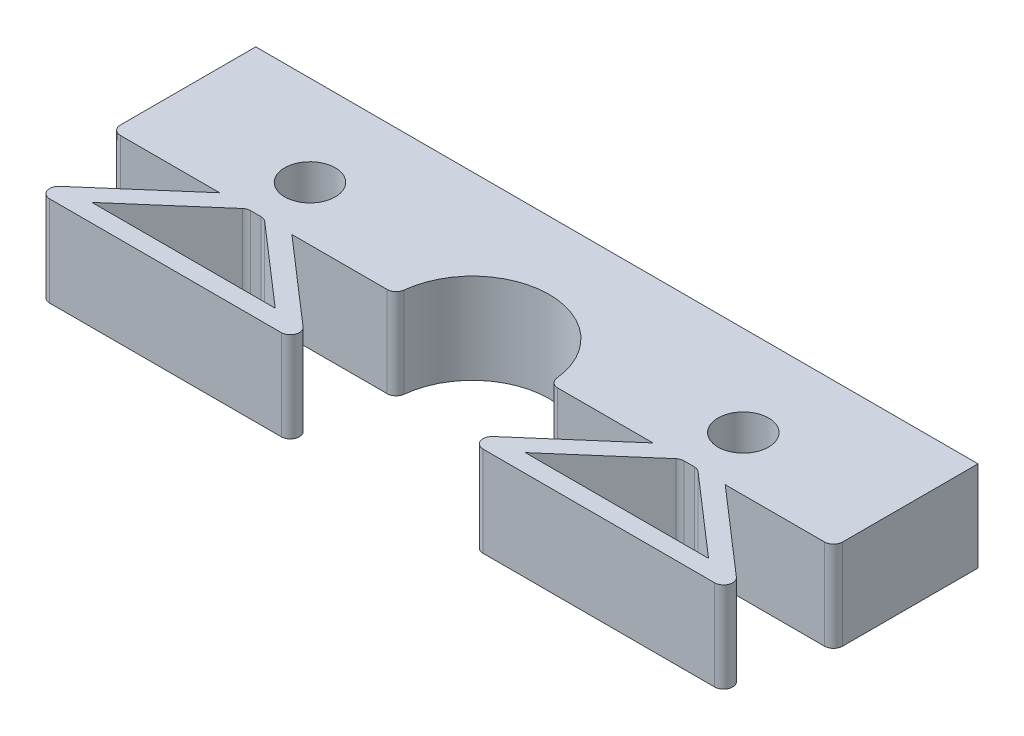
SolidWorks part; units mm, degrees
ref_plane "Front Plane" through (0, 0, 0) normal (0, 0, 1) x (1, 0, 0)
ref_plane "Top Plane" through (0, 0, 0) normal (0, 1, 0) x (1, 0, 0)
ref_plane "Right Plane" through (0, 0, 0) normal (1, 0, 0) x (0, 0, -1)
sketch "Sketch1" plane through (0, 0, 0) normal (0, 1, 0) x (1, 0, 0)
  line L1 (-20, 8) -> (20, 8)
  line L2 (20, 8) -> (20, 0)
  line L8 (4.25, -5) -> (10, 0)
  line L9 (10, 0) -> (-10, 0)
  line L10 (19.75, -5) -> (14, 0)
  line L11 (14, 0) -> (20, 0)
  line L15 (12.476, 0) -> (11.524, 0)
  line L17 (11.524, 0) -> (6.924, -4)
  line L18 (6.924, -4) -> (17.076, -4)
  line L19 (17.076, -4) -> (12.476, 0)
  line L20 (4.25, -5) -> (19.75, -5)
  line L21 (0, 8) -> (0, 0) construction
  line L23 (0, 0) -> (0, 20.8018) construction
  line L24 (-4.25, -5) -> (-10, 0)
  line L25 (-12.476, 0) -> (-11.524, 0)
  line L26 (-11.524, 0) -> (-6.924, -4)
  line L27 (-6.924, -4) -> (-17.076, -4)
  line L28 (-17.076, -4) -> (-12.476, 0)
  line L29 (-4.25, -5) -> (-19.75, -5)
  line L30 (-19.75, -5) -> (-14, 0)
  line L31 (-14, 0) -> (-20, 0)
  line L32 (-20, 8) -> (-20, 0)
  circle A0 centre (12, 3) radius 1.4
  circle A1 centre (-12, 3) radius 1.4
  point P0 (12, -5)
  point P1 (12, -4)
  point P4 (12, 0)
  point P30 (4, -6)
  point P31 (4, -6)
  point P34 (0, 0)
  point P35 (4, -6)
  point P36 (20, -6)
  point P37 (0, 0)
  point P38 (6.8382, -5.1071)
  point P39 (4, -5.93)
  point P40 (20, -6.0398)
  point P41 (0, 0)
  point P42 (19.1485, -6.0184)
  point P43 (9.6454, 0)
  point P44 (15.0291, 0)
  point P45 (0, 0)
  point P46 (6.2388, -6.7393)
  dimension "D10" = 2.8
  dimension "D1" = 20
  dimension "D2" = 4.25
  dimension "D3" = 8
  dimension "D4" = 1
  dimension "D5" = 6
  dimension "D6" = 1
  dimension "D7" = 5
  dimension "D9" = 5
  dimension "D11" = 12
extrude "Boss-Extrude1" add sketch "Sketch1" along normal blind 5
sketch "Sketch2" plane through (0, 5, 0) normal (0, 1, 0) x (1, 0, 0)
  line L0 (-10, 0) -> (10, 0) construction
  line L1 (-4.25, 0) -> (4.25, 0)
  arc A0 (-4.25, 0) -> (4.25, 0) centre (0, 0) cw
  dimension "D1" = 4.25
extrude "Cut-Extrude1" cut sketch "Sketch2" against normal through all
fillet "Fillet1" radius 0.5 12 edges at (19.75, 2.5, 5) (4.25, 2.5, 5) (-4.25, 2.5, 5) (-19.75, 2.5, 5) (20, 2.5, 0) (-4.25, 2.5, 0) (4.25, 2.5, 0) (-20, 2.5, 0) (-11.524, 2.5, 0) (-12.476, 2.5, 0) (12.476, 2.5, 0) (11.524, 2.5, 0)
